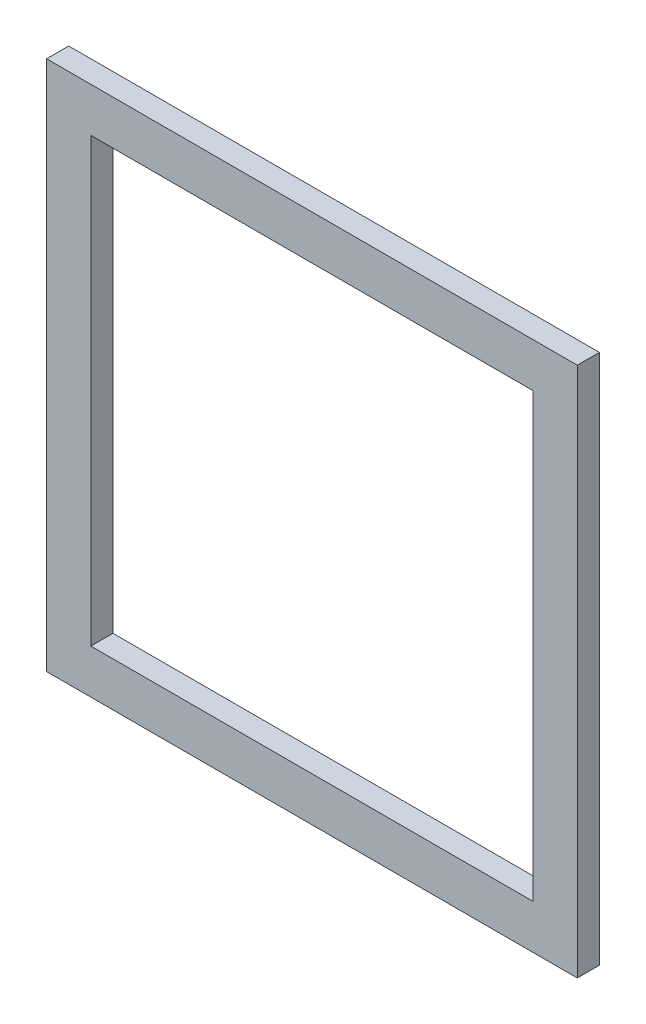
SolidWorks part; units mm, degrees
ref_plane "Front Plane" through (0, 0, 0) normal (0, 0, 1) x (1, 0, 0)
ref_plane "Top Plane" through (0, 0, 0) normal (0, 1, 0) x (1, 0, 0)
ref_plane "Right Plane" through (0, 0, 0) normal (1, 0, 0) x (0, 0, -1)
sketch "Sketch1" plane through (0, 0, 0) normal (0, 0, 1) x (1, 0, 0)
  line L1 (0, 0) -> (76.2, 0)
  line L2 (0, 0) -> (0, 76.2)
  line L3 (0, 76.2) -> (76.2, 76.2)
  line L4 (76.2, 0) -> (76.2, 76.2)
  dimension "D1" = 76.2
  dimension "D2" = 76.2
extrude "Boss-Extrude1" add sketch "Sketch1" along normal blind 3.175
sketch "Sketch2" plane through (0, 0, 3.175) normal (0, 0, 1) x (1, 0, 0)
  line L0 (0, 76.2) -> (0, 0) construction
  line L1 (6.35, 69.85) -> (69.85, 69.85)
  line L2 (6.35, 69.85) -> (6.35, 6.35)
  line L3 (6.35, 6.35) -> (69.85, 6.35)
  line L4 (69.85, 69.85) -> (69.85, 6.35)
  line L5 (76.2, 76.2) -> (0, 76.2) construction
  line L6 (76.2, 0) -> (76.2, 76.2) construction
  line L7 (0, 0) -> (76.2, 0) construction
  dimension "D1" = 6.35
  dimension "D2" = 6.35
  dimension "D3" = 6.35
  dimension "D4" = 6.35
extrude "Cut-Extrude1" cut sketch "Sketch2" against normal blind 3.175
